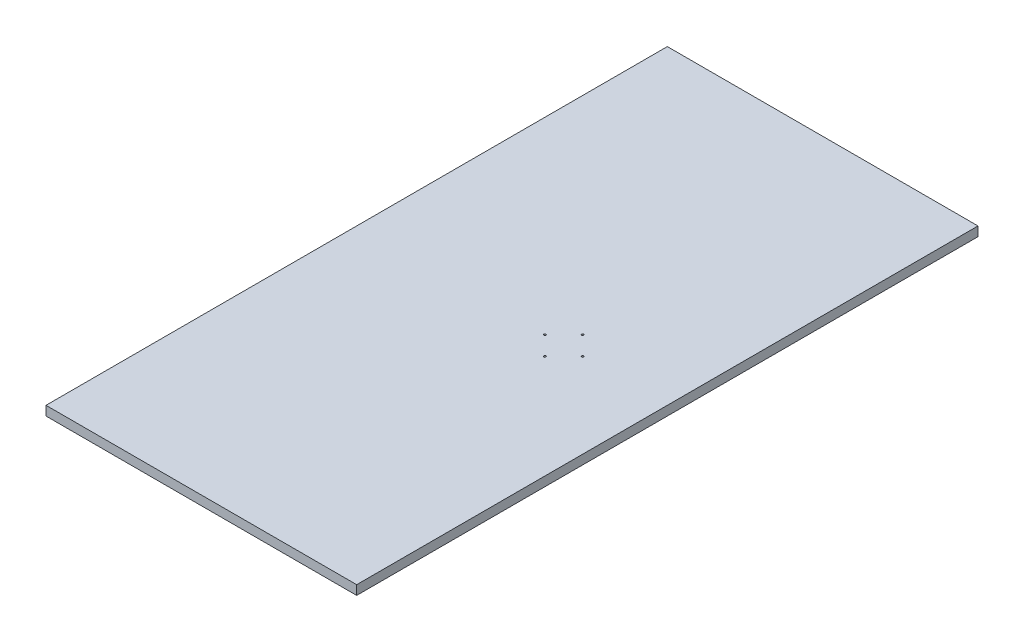
SolidWorks part; units mm, degrees
material "Oak"
ref_plane "Front Plane" through (0, 0, 0) normal (0, 0, 1) x (1, 0, 0)
ref_plane "Top Plane" through (0, 0, 0) normal (0, 1, 0) x (1, 0, 0)
ref_plane "Right Plane" through (0, 0, 0) normal (1, 0, 0) x (0, 0, -1)
sketch "Sketch1" plane through (0, 0, 0) normal (0, 1, 0) x (1, 0, 0)
  line L1 (-300, -600) -> (300, -600)
  line L2 (-300, -600) -> (-300, 600)
  line L3 (-300, 600) -> (300, 600)
  line L4 (300, -600) -> (300, 600)
  line L5 (-300, -600) -> (300, 600) construction
  line L6 (-300, 600) -> (300, -600) construction
  point P0 (0, 0)
  dimension "D1" = 600
  dimension "D2" = 1200
extrude "Boss-Extrude1" add sketch "Sketch1" along normal blind 18
sketch "Sketch2" plane through (0, 18, 0) normal (0, 1, 0) x (1, 0, 0)
  line L0 (300, -600) -> (300, 600) construction
  line L1 (300, 600) -> (-300, 600) construction
  line L2 (-300, -600) -> (300, -600) construction
  circle A0 centre (0, 350) radius 6
  circle A1 centre (100, -500) radius 6
  dimension "D1" = 300
  dimension "D2" = 250
  dimension "D3" = 12
  dimension "D4" = 200
  dimension "D5" = 100
  dimension "D6" = 12
sketch "Sketch3" plane through (0, 18, 0) normal (0, 1, 0) x (1, 0, 0)
  line L0 (300, -600) -> (300, 600) construction
  line L1 (300, 600) -> (-300, 600) construction
  line L3 (-300, -600) -> (300, -600) construction
  circle A0 centre (100, 0) radius 36.5 construction
  circle A1 centre (100, 36.5) radius 2
  circle A2 centre (100, -36.5) radius 2
  circle A3 centre (136.5, 0) radius 2
  circle A4 centre (63.5, 0) radius 2
  dimension "D2" = 73
  dimension "D3" = 4
  dimension "D4" = 4
  dimension "D5" = 4
  dimension "D6" = 4
  dimension "D7" = 600
  dimension "D1" = 200
extrude "Cut-Extrude1" cut sketch "Sketch3" against normal through all
sketch "Sketch4" [suppressed] plane through (0, 18, 0) normal (0, 1, 0) x (1, 0, 0)
  line L0 (300, -600) -> (300, 600) construction
  line L1 (-300, -600) -> (300, -600) construction
  circle A0 centre (150, 0) radius 36.5
  circle A1 centre (150, -36.5) radius 2
  circle A2 centre (113.5, 0) radius 2
  circle A3 centre (150, 36.5) radius 2
  circle A4 centre (186.5, 0) radius 2
  dimension "D1" = 73
  dimension "D2" = 150
  dimension "D3" = 600
  dimension "D4" = 4
  dimension "D5" = 4
  dimension "D6" = 4
  dimension "D7" = 4
extrude "Cut-Extrude2" [suppressed] cut sketch "Sketch4" against normal through all contours A1 | A2 | A3 | A4
sketch "Sketch5" [suppressed] plane through (0, 18, 0) normal (0, 1, 0) x (1, 0, 0)
  line L0 (300, -600) -> (300, 600) construction
  line L1 (-300, -600) -> (300, -600) construction
  line L2 (300, 600) -> (-300, 600) construction
  circle A0 centre (100, -450) radius 6
  circle A1 centre (150, 400) radius 6
  dimension "D1" = 12
  dimension "D2" = 200
  dimension "D3" = 150
  dimension "D4" = 150
  dimension "D5" = 200
  dimension "D6" = 12
